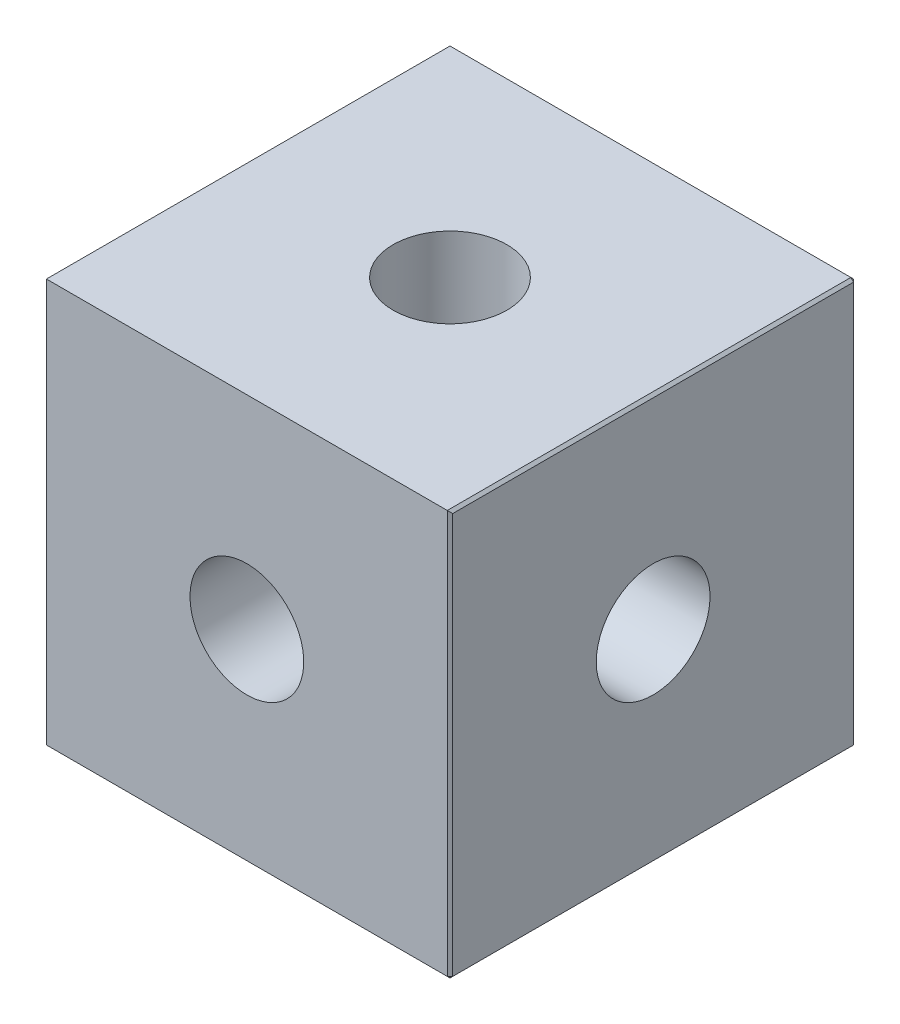
SolidWorks part; units mm, degrees
ref_plane "Front Plane" through (0, 0, 0) normal (0, 0, 1) x (1, 0, 0)
ref_plane "Top Plane" through (0, 0, 0) normal (0, 1, 0) x (1, 0, 0)
ref_plane "Right Plane" through (0, 0, 0) normal (1, 0, 0) x (0, 0, -1)
other "Configuration Table"
sketch "草图1" plane through (0, 0, 0) normal (0, 1, 0) x (1, 0, 0)
  line L1 (-7.5, 7.5) -> (7.5, 7.5)
  line L2 (-7.5, 7.5) -> (-7.5, -7.5)
  line L3 (-7.5, -7.5) -> (7.5, -7.5)
  line L4 (7.5, 7.5) -> (7.5, -7.5)
  line L5 (-7.5, 7.5) -> (7.5, -7.5) construction
  line L6 (-7.5, -7.5) -> (7.5, 7.5) construction
  point P0 (0, 0)
extrude "凸台-拉伸1" add sketch "草图1" along normal blind 15
sketch "草图6" plane through (0, 15, 0) normal (0, 1, 0) x (1, 0, 0)
  point P0 (0, 0)
hole_wizard "M5x0.8 螺纹孔1" positions "草图6" profile "草图5" tap size "M5x0.8" standard "ANSI Metric" end condition through all
sketch "草图5" plane through (0, 15, 0) normal (1, 0, 0) x (0, 0, 1)
  line L0 (0, 0) -> (0, 15)
  line L1 (0, 15) -> (2.1, 15)
  line L2 (2.1, 15) -> (2.1, 0)
  line L5 (2.1, 0) -> (0, 0)
  line L11 (0, -6.35) -> (0, 107.95) construction
  dimension "通孔螺纹孔钻头直径" = 4.2
  dimension "通孔螺纹孔钻头深度" = 15
cosmetic thread "孔螺纹线1" parameters "D2"=5
sketch "草图9" plane through (0, 0, -7.5) normal (0, 0, -1) x (-1, 0, 0)
  line L0 (-7.5, 7.5) -> (7.5, 7.5) construction
  line L1 (-7.5, 15) -> (-7.5, 0) construction
  line L2 (7.5, 15) -> (7.5, 0) construction
sketch "草图12" plane through (0, 0, -7.5) normal (0, 0, -1) x (-1, 0, 0)
  line L0 (-7.5, 7.5) -> (7.5, 7.5) construction
  point P0 (0, 7.5)
hole_wizard "M5x0.8 螺纹孔2" positions "草图12" profile "草图11" tap size "M5x0.8" standard "ANSI Metric" end condition through all
sketch "草图11" plane through (0, 7.5, -7.5) normal (1, 0, 0) x (0, 1, 0)
  line L0 (0, 0) -> (0, 15)
  line L1 (0, 15) -> (2.1, 15)
  line L2 (2.1, 15) -> (2.1, 0)
  line L5 (2.1, 0) -> (0, 0)
  line L11 (0, -6.35) -> (0, 107.95) construction
  dimension "通孔螺纹孔钻头直径" = 4.2
  dimension "通孔螺纹孔钻头深度" = 15
cosmetic thread "孔螺纹线2" parameters "D2"=5
sketch "草图13" plane through (-7.5, 0, 0) normal (-1, 0, 0) x (0, 0, 1)
  line L0 (-7.5, 7.5) -> (7.5, 7.5) construction
  line L1 (-7.5, 15) -> (-7.5, 0) construction
  line L2 (7.5, 15) -> (7.5, 0) construction
sketch "草图16" plane through (-7.5, 0, 0) normal (-1, 0, 0) x (0, 0, 1)
  line L0 (-7.5, 7.5) -> (7.5, 7.5) construction
  point P0 (0, 7.5)
hole_wizard "M5x0.8 螺纹孔3" positions "草图16" profile "草图15" tap size "M5x0.8" standard "ANSI Metric" end condition through all
sketch "草图15" plane through (-7.5, 7.5, 0) normal (0, 1, 0) x (0, 0, 1)
  line L0 (0, 0) -> (0, 15)
  line L1 (0, 15) -> (2.1, 15)
  line L2 (2.1, 15) -> (2.1, 0)
  line L5 (2.1, 0) -> (0, 0)
  line L11 (0, -6.35) -> (0, 107.95) construction
  dimension "通孔螺纹孔钻头直径" = 4.2
  dimension "通孔螺纹孔钻头深度" = 15
cosmetic thread "孔螺纹线3" parameters "D2"=5
chamfer "倒角1" distance 0.1 angle 45 11 edges at (7.5, 15, 0) (0, 15, -7.5) (7.5, 7.5, -7.5) (0, 0, -7.5) (7.5, 0, 0) (7.5, 7.5, 7.5) (0, 0, 7.5) (-7.5, 0, 0) (-7.5, 7.5, 7.5) (-7.5, 15, 0) (-7.5, 7.5, -7.5)
